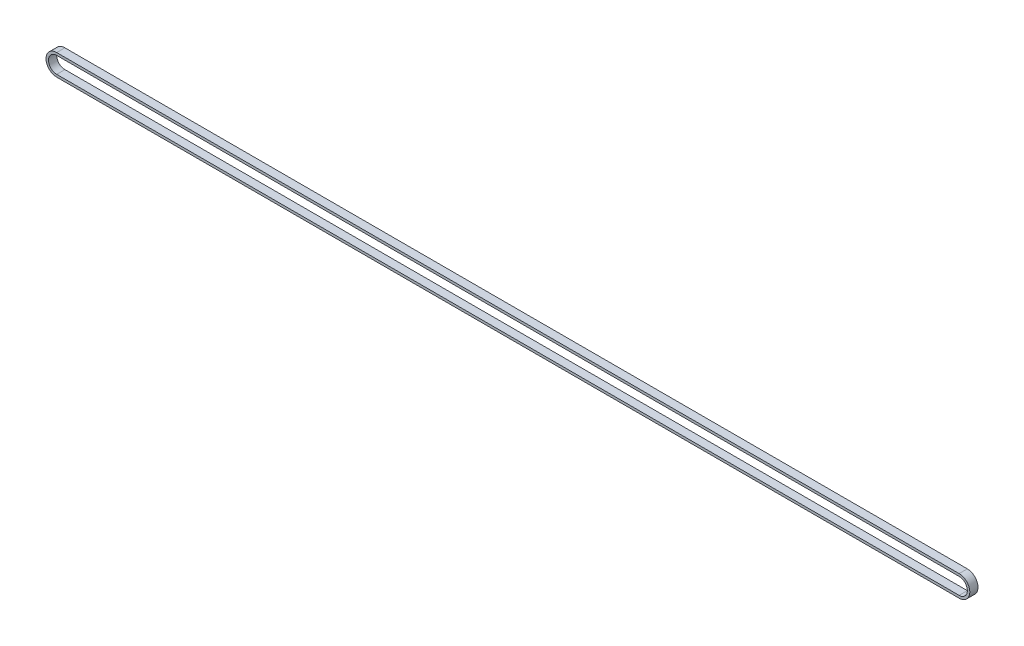
SolidWorks part; units mm, degrees
material "BUTYL"
ref_plane "Front Plane" through (0, 0, 0) normal (0, 0, 1) x (1, 0, 0)
ref_plane "Top Plane" through (0, 0, 0) normal (0, 1, 0) x (1, 0, 0)
ref_plane "Right Plane" through (0, 0, 0) normal (1, 0, 0) x (0, 0, -1)
sketch "Sketch1" plane through (0, 0, 0) normal (0, 0, 1) x (1, 0, 0)
  line L1 (-550, -10) -> (550, -10)
  line L2 (-550, 10) -> (550, 10)
  line L4 (0, 10) -> (0, -10) construction
  line L5 (-550, 0) -> (550, 0) construction
  line L6 (-550, 0) -> (-550, 10) construction
  line L7 (-550, 13) -> (550, 13)
  line L8 (-550, -13) -> (550, -13)
  arc A0 (-550, 10) -> (-550, -10) centre (-550, 0) ccw
  arc A1 (550, -10) -> (550, 10) centre (550, 0) ccw
  arc A2 (550, -13) -> (550, 13) centre (550, 0) ccw
  arc A3 (-550, 13) -> (-550, -13) centre (-550, 0) ccw
  point P1 (0, 0)
  dimension "D4" = 3
  dimension "D1" = 20
  dimension "D2" = 1100
  dimension "D3" = 10
extrude "Boss-Extrude1" add sketch "Sketch1" along normal blind 10
